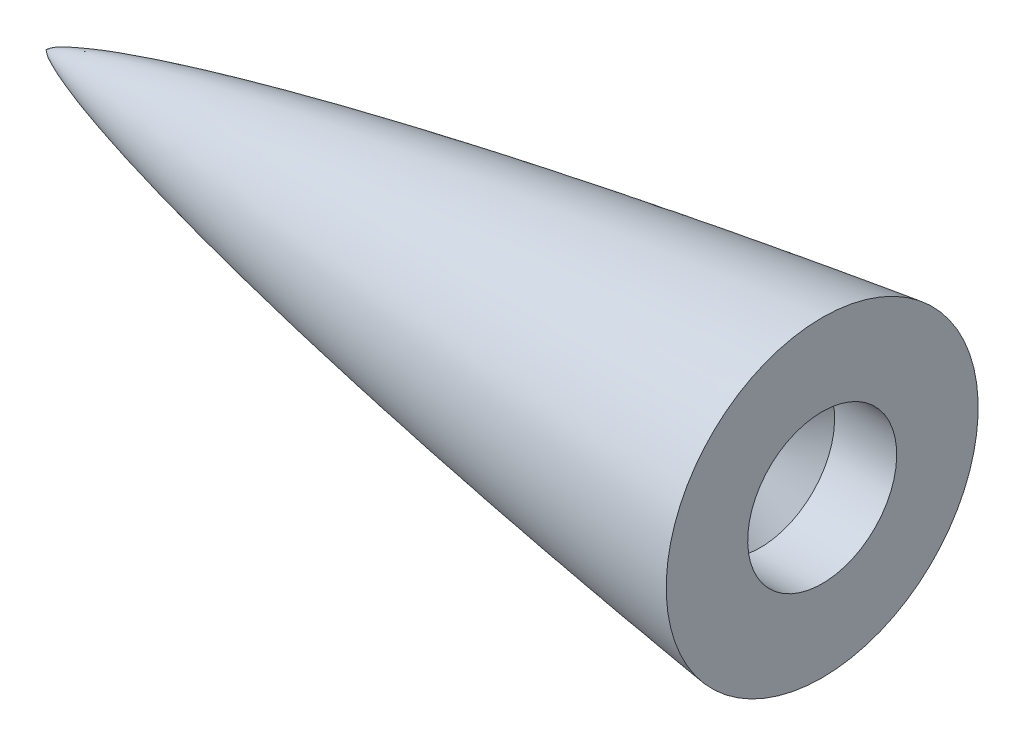
SolidWorks part; units mm, degrees
ref_plane "Front Plane" through (0, 0, 0) normal (0, 0, 1) x (1, 0, 0)
ref_plane "Top Plane" through (0, 0, 0) normal (0, 1, 0) x (1, 0, 0)
ref_plane "Right Plane" through (0, 0, 0) normal (1, 0, 0) x (0, 0, -1)
curve "Curve1"
  spline degree 3 poles (0, 0, 0) (0.3238, 0.2558, 0) (0.9402, 0.7427, 0) (1.9959, 1.205, 0) (2.9891, 1.6586, 0) (3.9977, 2.0398, 0) (4.9964, 2.4132, 0) (5.9986, 2.7607, 0) (6.9987, 3.1004, 0) (7.9965, 3.4344, 0) (9.0008, 3.7373, 0) (9.9965, 4.055, 0) (11.0004, 4.3386, 0) (12, 4.6299, 0) (12.9986, 4.9215, 0) (13.9986, 5.202, 0) (15.0003, 5.4688, 0) (15.9984, 5.7426, 0) (17.0001, 5.9995, 0) (18.0001, 6.2594, 0) (18.9985, 6.5227, 0) (20.0004, 6.7686, 0) (20.9985, 7.0227, 0) (22.0002, 7.2591, 0) (22.9999, 7.5005, 0) (24.0003, 7.7389, 0) (24.9983, 7.9838, 0) (26.0019, 8.205, 0) (26.9969, 8.4568, 0) (28.0017, 8.6659, 0) (28.9999, 8.9005, 0) (29.9988, 9.1322, 0) (31.0001, 9.3496, 0) (32.0002, 9.5692, 0) (32.9985, 9.7935, 0) (34.0016, 9.9959, 0) (34.9985, 10.2236, 0) (36.0002, 10.4289, 0) (36.9999, 10.6405, 0) (38.0002, 10.8489, 0) (38.9986, 11.0636, 0) (40.0015, 11.2559, 0) (40.9986, 11.4736, 0) (42.0002, 11.6689, 0) (42.9999, 11.8705, 0) (44.0002, 12.0689, 0) (44.9986, 12.2737, 0) (46.0015, 12.4556, 0) (46.9985, 12.6646, 0) (48.0015, 12.8456, 0) (48.9986, 13.0537, 0) (50.0002, 13.2389, 0) (50.9999, 13.4305, 0) (52.0002, 13.619, 0) (52.9988, 13.8134, 0) (54.0012, 13.9868, 0) (55, 14.1802, 0) (55.9989, 14.3724, 0) (57.0001, 14.5493, 0) (58, 14.7302, 0) (59, 14.9099, 0) (60, 15.09, 0) (61, 15.2699, 0) (62, 15.4503, 0) (63.0002, 15.629, 0) (63.9988, 15.8137, 0) (65.0013, 15.9758, 0) (65.9988, 16.1637, 0) (67.0002, 16.329, 0) (68, 16.5003, 0) (69, 16.6699, 0) (70, 16.84, 0) (71, 17.01, 0) (72, 17.1799, 0) (73, 17.3503, 0) (74.0002, 17.519, 0) (74.9988, 17.6937, 0) (76.0012, 17.8458, 0) (76.9989, 18.0234, 0) (78, 18.1799, 0) (79.0011, 18.3368, 0) (79.9989, 18.5134, 0) (81.0002, 18.6691, 0) (82, 18.8303, 0) (83, 18.9899, 0) (84, 19.1503, 0) (85.0001, 19.3091, 0) (85.999, 19.4734, 0) (87.001, 19.6168, 0) (88, 19.78, 0) (88.999, 19.9434, 0) (90.0012, 20.0859, 0) (90.999, 20.2534, 0) (92, 20.4, 0) (93.001, 20.5468, 0) (93.999, 20.7134, 0) (95.0001, 20.8591, 0) (96, 21.0103, 0) (97, 21.1599, 0) (98, 21.3103, 0) (99.0001, 21.4591, 0) (99.999, 21.6134, 0) (101.001, 21.7468, 0) (102, 21.8999, 0) (102.999, 22.0535, 0) (104.0011, 22.1855, 0) (104.9988, 22.3446, 0) (106.0011, 22.4755, 0) (106.999, 22.6335, 0) (108, 22.7699, 0) (109.001, 22.9068, 0) (109.999, 23.0634, 0) (111.0001, 23.1991, 0) (112, 23.3402, 0) (113, 23.48, 0) (114, 23.62, 0) (115, 23.7602, 0) (116.0001, 23.8991, 0) (116.9991, 24.0435, 0) (118.0009, 24.1667, 0) (119, 24.3099, 0) (119.9991, 24.4535, 0) (121.0011, 24.5755, 0) (121.9989, 24.7247, 0) (123.0011, 24.8455, 0) (123.9991, 24.9935, 0) (125, 25.1199, 0) (126.0009, 25.2467, 0) (126.9991, 25.3935, 0) (128.0001, 25.5191, 0) (129, 25.6503, 0) (130, 25.7799, 0) (131, 25.91, 0) (132, 26.0399, 0) (133, 26.1703, 0) (134.0001, 26.2991, 0) (134.9991, 26.4335, 0) (136.0008, 26.5467, 0) (137, 26.6799, 0) (137.9991, 26.8136, 0) (139.001, 26.9255, 0) (139.999, 27.0647, 0) (141.001, 27.1755, 0) (141.9991, 27.3136, 0) (143, 27.4299, 0) (144.0008, 27.5467, 0) (144.9991, 27.6835, 0) (146.0001, 27.7991, 0) (147, 27.9203, 0) (148, 28.0399, 0) (149, 28.16, 0) (150, 28.28, 0) (151, 28.4, 0) (152, 28.52, 0) (153, 28.6399, 0) (154, 28.7603, 0) (155.0001, 28.879, 0) (155.9992, 29.0038, 0) (157.0009, 29.1054, 0) (157.9991, 29.2348, 0) (159.0009, 29.3351, 0) (159.9991, 29.4649, 0) (161.0009, 29.5651, 0) (161.9991, 29.6948, 0) (163.0009, 29.7954, 0) (163.9992, 29.9238, 0) (165.0001, 30.029, 0) (166, 30.1403, 0) (167, 30.2499, 0) (168, 30.36, 0) (169, 30.47, 0) (170, 30.58, 0) (171, 30.69, 0) (172, 30.8, 0) (173, 30.9099, 0) (174, 31.0203, 0) (175.0001, 31.129, 0) (175.9992, 31.2439, 0) (177.0008, 31.3354, 0) (177.9991, 31.4548, 0) (179.0009, 31.5451, 0) (179.9991, 31.6649, 0) (181.0009, 31.7551, 0) (181.9991, 31.8748, 0) (183.0008, 31.9654, 0) (183.9992, 32.0838, 0) (185.0001, 32.179, 0) (186, 32.28, 0) (186.9999, 32.3809, 0) (188.0007, 32.4765, 0) (188.9993, 32.5935, 0) (190.0001, 32.6893, 0) (191.0001, 32.7893, 0) (191.9993, 32.8935, 0) (193.0007, 32.9764, 0) (193.9999, 33.0812, 0) (195.0001, 33.1788, 0) (195.9993, 33.2836, 0) (197.0006, 33.3667, 0) (198, 33.4699, 0) (198.9993, 33.5736, 0) (200.0007, 33.6554, 0) (200.9992, 33.7648, 0) (202.0008, 33.8454, 0) (202.9993, 33.9539, 0) (204.0001, 34.0387, 0) (204.9999, 34.1313, 0) (206.0007, 34.2163, 0) (206.9993, 34.3236, 0) (208.0001, 34.409, 0) (209, 34.5003, 0) (210, 34.5899, 0) (211, 34.6803, 0) (212.0001, 34.769, 0) (212.9994, 34.8635, 0) (214.0006, 34.9366, 0) (215, 35.03, 0) (215.9994, 35.1233, 0) (217.0006, 35.1967, 0) (218, 35.2899, 0) (218.9994, 35.3835, 0) (220.0006, 35.4558, 0) (220.9994, 35.5535, 0) (222, 35.6299, 0) (223.0006, 35.7067, 0) (223.9994, 35.8035, 0) (225.0001, 35.879, 0) (226, 35.9603, 0) (227, 36.0399, 0) (228, 36.12, 0) (229, 36.2, 0) (230, 36.2799, 0) (231, 36.3603, 0) (232.0001, 36.439, 0) (232.9995, 36.5235, 0) (234.0005, 36.5867, 0) (235, 36.6699, 0) (235.9995, 36.7535, 0) (237.0006, 36.8157, 0) (237.9995, 36.9035, 0) (239, 36.9699, 0) (240.0005, 37.0367, 0) (240.9995, 37.1235, 0) (242.0001, 37.189, 0) (243, 37.2603, 0) (244, 37.3299, 0) (245, 37.4, 0) (246, 37.47, 0) (247, 37.5399, 0) (248, 37.6103, 0) (249.0001, 37.6789, 0) (249.9995, 37.7539, 0) (251.0005, 37.8053, 0) (251.9995, 37.8849, 0) (253.0005, 37.9351, 0) (253.9995, 38.0149, 0) (255.0005, 38.0653, 0) (255.9995, 38.1439, 0) (257.0001, 38.1989, 0) (258, 38.2603, 0) (259, 38.3199, 0) (260, 38.38, 0) (261, 38.4399, 0) (262, 38.5003, 0) (263.0001, 38.5589, 0) (263.9996, 38.6239, 0) (265.0004, 38.6653, 0) (265.9995, 38.7349, 0) (267.0005, 38.7751, 0) (267.9995, 38.8449, 0) (269.0004, 38.8853, 0) (269.9996, 38.9539, 0) (271.0001, 38.999, 0) (272, 39.0502, 0) (273, 39.1002, 0) (274, 39.1491, 0) (274.9997, 39.2036, 0) (276.0003, 39.2365, 0) (277, 39.2903, 0) (277.9997, 39.3424, 0) (279, 39.3803, 0) (280.0003, 39.4166, 0) (280.9997, 39.4735, 0) (282, 39.5093, 0) (283, 39.5493, 0) (283.9998, 39.5935, 0) (285.0002, 39.6166, 0) (286, 39.6602, 0) (286.9998, 39.7026, 0) (288, 39.7293, 0) (289, 39.7602, 0) (290, 39.7899, 0) (291, 39.8203, 0) (292, 39.849, 0) (292.9998, 39.8839, 0) (294.0002, 39.8955, 0) (294.9998, 39.9341, 0) (296, 39.9482, 0) (296.9999, 39.9732, 0) (298, 39.9792, 0) (299, 39.9902, 0) (299.6667, 39.9967, 0) (300, 40, 0) knots 0 0 0 0 0.004059 0.007728 0.011327 0.014863 0.018375 0.021865 0.025345 0.028814 0.032263 0.035712 0.039142 0.042572 0.046002 0.049423 0.052835 0.056247 0.059651 0.063054 0.066458 0.069854 0.07325 0.076637 0.080025 0.083413 0.086801 0.090181 0.093569 0.096942 0.100322 0.103702 0.107075 0.110448 0.113821 0.117187 0.120561 0.123927 0.127293 0.130659 0.134025 0.137384 0.140751 0.14411 0.147469 0.150829 0.154188 0.157542 0.160901 0.164254 0.167614 0.170967 0.17432 0.177673 0.181027 0.184374 0.187727 0.19108 0.194427 0.197774 0.201122 0.204469 0.207816 0.211163 0.21451 0.217858 0.221199 0.224546 0.227888 0.231229 0.234571 0.237912 0.241254 0.244595 0.247937 0.251278 0.25462 0.257956 0.261298 0.264634 0.26797 0.271311 0.274648 0.277984 0.28132 0.284656 0.287992 0.291328 0.294659 0.297995 0.301332 0.304663 0.307999 0.31133 0.314661 0.317997 0.321328 0.324659 0.327991 0.331322 0.334653 0.337984 0.34131 0.344641 0.347972 0.351299 0.35463 0.357956 0.361287 0.364614 0.36794 0.371271 0.374598 0.377924 0.38125 0.384577 0.387903 0.391229 0.394556 0.397878 0.401204 0.404531 0.407853 0.411179 0.414501 0.417827 0.421149 0.424471 0.427798 0.43112 0.434442 0.437763 0.441085 0.444407 0.447729 0.451051 0.454373 0.457691 0.461013 0.464335 0.467653 0.470975 0.474293 0.477615 0.480933 0.484251 0.487573 0.49089 0.494208 0.497526 0.500844 0.504162 0.50748 0.510798 0.514116 0.517434 0.520751 0.524069 0.527383 0.530701 0.534015 0.537333 0.540647 0.543965 0.547279 0.550597 0.553911 0.557226 0.56054 0.563854 0.567168 0.570482 0.573796 0.57711 0.580424 0.583738 0.587053 0.590367 0.593677 0.596991 0.600302 0.603616 0.606927 0.610241 0.613552 0.616866 0.620177 0.623487 0.626798 0.630109 0.633423 0.636733 0.640044 0.643355 0.646662 0.649973 0.653284 0.656594 0.659902 0.663213 0.666523 0.669831 0.673142 0.676449 0.67976 0.683067 0.686375 0.689682 0.692993 0.696301 0.699608 0.702916 0.706223 0.709531 0.712838 0.716143 0.719451 0.722758 0.726063 0.729371 0.732678 0.735983 0.739291 0.742595 0.7459 0.749208 0.752513 0.755817 0.759122 0.762427 0.765732 0.769036 0.772341 0.775646 0.778951 0.782253 0.785558 0.788863 0.792165 0.79547 0.798772 0.802074 0.805379 0.808681 0.811984 0.815286 0.818588 0.821891 0.825193 0.828495 0.831797 0.8351 0.8384 0.841702 0.845002 0.848305 0.851605 0.854907 0.858207 0.861508 0.864808 0.868108 0.871408 0.874708 0.878008 0.881309 0.884607 0.887907 0.891206 0.894506 0.897804 0.901104 0.904403 0.907701 0.910999 0.914298 0.917596 0.920893 0.924191 0.92749 0.930787 0.934083 0.937382 0.940679 0.943976 0.947272 0.950568 0.953865 0.957162 0.960458 0.963753 0.967049 0.970345 0.973641 0.976936 0.980231 0.983527 0.986822 0.990117 0.993411 0.996706 1 1 1 1
sketch "Sketch1" plane through (0, 0, 0) normal (0, 0, 1) x (1, 0, 0)
  line L0 (125, 25.12) -> (125, 3.175)
  line L1 (21.825, 0) -> (0, 0)
  line L2 (1366, 0) -> (125, 0) construction
  line L3 (125, 3.175) -> (25, 3.175)
  line L4 (25, 3.175) -> (21.825, 0)
  line L5 (21.825, 0) -> (-59.4496, 0) construction
  line L6 (125, 12) -> (115, 12)
  line L7 (115, 12) -> (106.175, 3.175)
  spline S0 degree 3 poles (-1070.3353, 1688.9679) (10.2744, -68.4827) (-11.5783, -4.7393) (1.9959, 1.205) (2.9891, 1.6586) (3.9977, 2.0398) (4.9964, 2.4132) (5.9986, 2.7607) (6.9987, 3.1004) (7.9965, 3.4344) (9.0008, 3.7373) (9.9965, 4.055) (11.0004, 4.3386) (12, 4.6299) (12.9986, 4.9215) (13.9986, 5.202) (15.0003, 5.4688) (15.9984, 5.7426) (17.0001, 5.9995) (18.0001, 6.2594) (18.9985, 6.5227) (20.0004, 6.7686) (20.9985, 7.0227) (22.0002, 7.2591) (22.9999, 7.5005) (24.0003, 7.7389) (24.9983, 7.9838) (26.0019, 8.205) (26.9969, 8.4568) (28.0017, 8.6659) (28.9999, 8.9005) (29.9988, 9.1322) (31.0001, 9.3496) (32.0002, 9.5692) (32.9985, 9.7935) (34.0016, 9.9959) (34.9985, 10.2236) (36.0002, 10.4289) (36.9999, 10.6405) (38.0002, 10.8489) (38.9986, 11.0636) (40.0015, 11.2559) (40.9986, 11.4736) (42.0002, 11.6689) (42.9999, 11.8705) (44.0002, 12.0689) (44.9986, 12.2737) (46.0015, 12.4556) (46.9985, 12.6646) (48.0015, 12.8456) (48.9986, 13.0537) (50.0002, 13.2389) (50.9999, 13.4305) (52.0002, 13.619) (52.9988, 13.8134) (54.0012, 13.9868) (55, 14.1802) (55.9989, 14.3724) (57.0001, 14.5493) (58, 14.7302) (59, 14.9099) (60, 15.09) (61, 15.2699) (62, 15.4503) (63.0002, 15.629) (63.9988, 15.8137) (65.0013, 15.9758) (65.9988, 16.1637) (67.0002, 16.329) (68, 16.5003) (69, 16.6699) (70, 16.84) (71, 17.01) (72, 17.1799) (73, 17.3503) (74.0002, 17.519) (74.9988, 17.6937) (76.0012, 17.8458) (76.9989, 18.0234) (78, 18.1799) (79.0011, 18.3368) (79.9989, 18.5134) (81.0002, 18.6691) (82, 18.8303) (83, 18.9899) (84, 19.1503) (85.0001, 19.3091) (85.999, 19.4734) (87.001, 19.6168) (88, 19.78) (88.999, 19.9434) (90.0012, 20.0859) (90.999, 20.2534) (92, 20.4) (93.001, 20.5468) (93.999, 20.7134) (95.0001, 20.8591) (96, 21.0103) (97, 21.1599) (98, 21.3103) (99.0001, 21.4591) (99.999, 21.6134) (101.001, 21.7468) (102, 21.8999) (102.999, 22.0535) (104.0011, 22.1855) (104.9988, 22.3446) (106.0011, 22.4755) (106.999, 22.6335) (108, 22.7699) (109.001, 22.9068) (109.999, 23.0634) (111.0001, 23.1991) (112, 23.3402) (113, 23.48) (114, 23.62) (115, 23.7602) (116.0001, 23.8991) (116.9991, 24.0435) (118.0009, 24.1667) (119, 24.3099) (119.9991, 24.4535) (121.0011, 24.5755) (121.9989, 24.7247) (123.0011, 24.8455) (123.9991, 24.9935) (125, 25.1199) (126.0009, 25.2467) (126.9991, 25.3935) (128.0001, 25.5191) (129, 25.6503) (130, 25.7799) (131, 25.91) (132, 26.0399) (133, 26.1703) (134.0001, 26.2991) (134.9991, 26.4335) (136.0008, 26.5467) (137, 26.6799) (137.9991, 26.8136) (139.001, 26.9255) (139.999, 27.0647) (141.001, 27.1755) (141.9991, 27.3136) (143, 27.4299) (144.0008, 27.5467) (144.9991, 27.6835) (146.0001, 27.7991) (147, 27.9203) (148, 28.0399) (149, 28.16) (150, 28.28) (151, 28.4) (152, 28.52) (153, 28.6399) (154, 28.7603) (155.0001, 28.879) (155.9992, 29.0038) (157.0009, 29.1054) (157.9991, 29.2348) (159.0009, 29.3351) (159.9991, 29.4649) (161.0009, 29.5651) (161.9991, 29.6948) (163.0009, 29.7954) (163.9992, 29.9238) (165.0001, 30.029) (166, 30.1403) (167, 30.2499) (168, 30.36) (169, 30.47) (170, 30.58) (171, 30.69) (172, 30.8) (173, 30.9099) (174, 31.0203) (175.0001, 31.129) (175.9992, 31.2439) (177.0008, 31.3354) (177.9991, 31.4548) (179.0009, 31.5451) (179.9991, 31.6649) (181.0009, 31.7551) (181.9991, 31.8748) (183.0008, 31.9654) (183.9992, 32.0838) (185.0001, 32.179) (186, 32.28) (186.9999, 32.3809) (188.0007, 32.4765) (188.9993, 32.5935) (190.0001, 32.6893) (191.0001, 32.7893) (191.9993, 32.8935) (193.0007, 32.9764) (193.9999, 33.0812) (195.0001, 33.1788) (195.9993, 33.2836) (197.0006, 33.3667) (198, 33.4699) (198.9993, 33.5736) (200.0007, 33.6554) (200.9992, 33.7648) (202.0008, 33.8454) (202.9993, 33.9539) (204.0001, 34.0387) (204.9999, 34.1313) (206.0007, 34.2163) (206.9993, 34.3236) (208.0001, 34.409) (209, 34.5003) (210, 34.5899) (211, 34.6803) (212.0001, 34.769) (212.9994, 34.8635) (214.0006, 34.9366) (215, 35.03) (215.9994, 35.1233) (217.0006, 35.1967) (218, 35.2899) (218.9994, 35.3835) (220.0006, 35.4558) (220.9994, 35.5535) (222, 35.6299) (223.0006, 35.7067) (223.9994, 35.8035) (225.0001, 35.879) (226, 35.9603) (227, 36.0399) (228, 36.12) (229, 36.2) (230, 36.2799) (231, 36.3603) (232.0001, 36.439) (232.9995, 36.5235) (234.0005, 36.5867) (235, 36.6699) (235.9995, 36.7535) (237.0006, 36.8157) (237.9995, 36.9035) (239, 36.9699) (240.0005, 37.0367) (240.9995, 37.1235) (242.0001, 37.189) (243, 37.2603) (244, 37.3299) (245, 37.4) (246, 37.47) (247, 37.5399) (248, 37.6103) (249.0001, 37.6789) (249.9995, 37.7539) (251.0005, 37.8053) (251.9995, 37.8849) (253.0005, 37.9351) (253.9995, 38.0149) (255.0005, 38.0653) (255.9995, 38.1439) (257.0001, 38.1989) (258, 38.2603) (259, 38.3199) (260, 38.38) (261, 38.4399) (262, 38.5003) (263.0001, 38.5589) (263.9996, 38.6239) (265.0004, 38.6653) (265.9995, 38.7349) (267.0005, 38.7751) (267.9995, 38.8449) (269.0004, 38.8853) (269.9996, 38.9539) (271.0001, 38.999) (272, 39.0502) (273, 39.1002) (274, 39.1491) (274.9997, 39.2036) (276.0003, 39.2365) (277, 39.2903) (277.9997, 39.3424) (279, 39.3803) (280.0003, 39.4166) (280.9997, 39.4735) (282, 39.5093) (283, 39.5493) (283.9998, 39.5935) (285.0002, 39.6166) (286, 39.6602) (286.9998, 39.7026) (288, 39.7293) (289, 39.7602) (290, 39.7899) (291, 39.8203) (292, 39.849) (292.9998, 39.8839) (294.0002, 39.8955) (294.9998, 39.9341) (296, 39.9482) (296.9999, 39.9732) (298, 39.9792) (369.4003, 40.7684) (440.6193, 31.9722) (479.6754, 2027.9914) knots -0.134313 -0.134313 -0.134313 -0.134313 0.004059 0.007728 0.011327 0.014863 0.018375 0.021865 0.025345 0.028814 0.032263 0.035712 0.039142 0.042572 0.046002 0.049423 0.052835 0.056247 0.059651 0.063054 0.066458 0.069854 0.07325 0.076637 0.080025 0.083413 0.086801 0.090181 0.093569 0.096942 0.100322 0.103702 0.107075 0.110448 0.113821 0.117187 0.120561 0.123927 0.127293 0.130659 0.134025 0.137384 0.140751 0.14411 0.147469 0.150829 0.154188 0.157542 0.160901 0.164254 0.167614 0.170967 0.17432 0.177673 0.181027 0.184374 0.187727 0.19108 0.194427 0.197774 0.201122 0.204469 0.207816 0.211163 0.21451 0.217858 0.221199 0.224546 0.227888 0.231229 0.234571 0.237912 0.241254 0.244595 0.247937 0.251278 0.25462 0.257956 0.261298 0.264634 0.26797 0.271311 0.274648 0.277984 0.28132 0.284656 0.287992 0.291328 0.294659 0.297995 0.301332 0.304663 0.307999 0.31133 0.314661 0.317997 0.321328 0.324659 0.327991 0.331322 0.334653 0.337984 0.34131 0.344641 0.347972 0.351299 0.35463 0.357956 0.361287 0.364614 0.36794 0.371271 0.374598 0.377924 0.38125 0.384577 0.387903 0.391229 0.394556 0.397878 0.401204 0.404531 0.407853 0.411179 0.414501 0.417827 0.421149 0.424471 0.427798 0.43112 0.434442 0.437763 0.441085 0.444407 0.447729 0.451051 0.454373 0.457691 0.461013 0.464335 0.467653 0.470975 0.474293 0.477615 0.480933 0.484251 0.487573 0.49089 0.494208 0.497526 0.500844 0.504162 0.50748 0.510798 0.514116 0.517434 0.520751 0.524069 0.527383 0.530701 0.534015 0.537333 0.540647 0.543965 0.547279 0.550597 0.553911 0.557226 0.56054 0.563854 0.567168 0.570482 0.573796 0.57711 0.580424 0.583738 0.587053 0.590367 0.593677 0.596991 0.600302 0.603616 0.606927 0.610241 0.613552 0.616866 0.620177 0.623487 0.626798 0.630109 0.633423 0.636733 0.640044 0.643355 0.646662 0.649973 0.653284 0.656594 0.659902 0.663213 0.666523 0.669831 0.673142 0.676449 0.67976 0.683067 0.686375 0.689682 0.692993 0.696301 0.699608 0.702916 0.706223 0.709531 0.712838 0.716143 0.719451 0.722758 0.726063 0.729371 0.732678 0.735983 0.739291 0.742595 0.7459 0.749208 0.752513 0.755817 0.759122 0.762427 0.765732 0.769036 0.772341 0.775646 0.778951 0.782253 0.785558 0.788863 0.792165 0.79547 0.798772 0.802074 0.805379 0.808681 0.811984 0.815286 0.818588 0.821891 0.825193 0.828495 0.831797 0.8351 0.8384 0.841702 0.845002 0.848305 0.851605 0.854907 0.858207 0.861508 0.864808 0.868108 0.871408 0.874708 0.878008 0.881309 0.884607 0.887907 0.891206 0.894506 0.897804 0.901104 0.904403 0.907701 0.910999 0.914298 0.917596 0.920893 0.924191 0.92749 0.930787 0.934083 0.937382 0.940679 0.943976 0.947272 0.950568 0.953865 0.957162 0.960458 0.963753 0.967049 0.970345 0.973641 0.976936 0.980231 0.983527 0.986822 0.990117 0.993411 0.996706 1.695794 1.695794 1.695794 1.695794 only from (0, 0) to (300, 40) construction
  spline S1 degree 3 poles (0, 0) (0.3238, 0.2558) (0.9402, 0.7427) (1.9959, 1.205) (2.9891, 1.6586) (3.9977, 2.0398) (4.9964, 2.4132) (5.9986, 2.7607) (6.9987, 3.1004) (7.9965, 3.4344) (9.0008, 3.7373) (9.9965, 4.055) (11.0004, 4.3386) (12, 4.6299) (12.9986, 4.9215) (13.9986, 5.202) (15.0003, 5.4688) (15.9984, 5.7426) (17.0001, 5.9995) (18.0001, 6.2594) (18.9985, 6.5227) (20.0004, 6.7686) (20.9985, 7.0227) (22.0002, 7.2591) (22.9999, 7.5005) (24.0003, 7.7389) (24.9983, 7.9838) (26.0019, 8.205) (26.9969, 8.4568) (28.0017, 8.6659) (28.9999, 8.9005) (29.9988, 9.1322) (31.0001, 9.3496) (32.0002, 9.5692) (32.9985, 9.7935) (34.0016, 9.9959) (34.9985, 10.2236) (36.0002, 10.4289) (36.9999, 10.6405) (38.0002, 10.8489) (38.9986, 11.0636) (40.0015, 11.2559) (40.9986, 11.4736) (42.0002, 11.6689) (42.9999, 11.8705) (44.0002, 12.0689) (44.9986, 12.2737) (46.0015, 12.4556) (46.9985, 12.6646) (48.0015, 12.8456) (48.9986, 13.0537) (50.0002, 13.2389) (50.9999, 13.4305) (52.0002, 13.619) (52.9988, 13.8134) (54.0012, 13.9868) (55, 14.1802) (55.9989, 14.3724) (57.0001, 14.5493) (58, 14.7302) (59, 14.9099) (60, 15.09) (61, 15.2699) (62, 15.4503) (63.0002, 15.629) (63.9988, 15.8137) (65.0013, 15.9758) (65.9988, 16.1637) (67.0002, 16.329) (68, 16.5003) (69, 16.6699) (70, 16.84) (71, 17.01) (72, 17.1799) (73, 17.3503) (74.0002, 17.519) (74.9988, 17.6937) (76.0012, 17.8458) (76.9989, 18.0234) (78, 18.1799) (79.0011, 18.3368) (79.9989, 18.5134) (81.0002, 18.6691) (82, 18.8303) (83, 18.9899) (84, 19.1503) (85.0001, 19.3091) (85.999, 19.4734) (87.001, 19.6168) (88, 19.78) (88.999, 19.9434) (90.0012, 20.0859) (90.999, 20.2534) (92, 20.4) (93.001, 20.5468) (93.999, 20.7134) (95.0001, 20.8591) (96, 21.0103) (97, 21.1599) (98, 21.3103) (99.0001, 21.4591) (99.999, 21.6134) (101.001, 21.7468) (102, 21.8999) (102.999, 22.0535) (104.0011, 22.1855) (104.9988, 22.3446) (106.0011, 22.4755) (106.999, 22.6335) (108, 22.7699) (109.001, 22.9068) (109.999, 23.0634) (111.0001, 23.1991) (112, 23.3402) (113, 23.48) (114, 23.62) (115, 23.7602) (116.0001, 23.8991) (116.9991, 24.0435) (118.0009, 24.1667) (119, 24.3099) (119.9991, 24.4535) (121.0011, 24.5755) (121.9989, 24.7247) (123.0011, 24.8455) (123.9991, 24.9935) (125, 25.1199) (126.0009, 25.2467) (126.9991, 25.3935) (128.0001, 25.5191) (129, 25.6503) (130, 25.7799) (131, 25.91) (132, 26.0399) (133, 26.1703) (134.0001, 26.2991) (134.9991, 26.4335) (136.0008, 26.5467) (137, 26.6799) (137.9991, 26.8136) (139.001, 26.9255) (139.999, 27.0647) (141.001, 27.1755) (141.9991, 27.3136) (143, 27.4299) (144.0008, 27.5467) (144.9991, 27.6835) (146.0001, 27.7991) (147, 27.9203) (148, 28.0399) (149, 28.16) (150, 28.28) (151, 28.4) (152, 28.52) (153, 28.6399) (154, 28.7603) (155.0001, 28.879) (155.9992, 29.0038) (157.0009, 29.1054) (157.9991, 29.2348) (159.0009, 29.3351) (159.9991, 29.4649) (161.0009, 29.5651) (161.9991, 29.6948) (163.0009, 29.7954) (163.9992, 29.9238) (165.0001, 30.029) (166, 30.1403) (167, 30.2499) (168, 30.36) (169, 30.47) (170, 30.58) (171, 30.69) (172, 30.8) (173, 30.9099) (174, 31.0203) (175.0001, 31.129) (175.9992, 31.2439) (177.0008, 31.3354) (177.9991, 31.4548) (179.0009, 31.5451) (179.9991, 31.6649) (181.0009, 31.7551) (181.9991, 31.8748) (183.0008, 31.9654) (183.9992, 32.0838) (185.0001, 32.179) (186, 32.28) (186.9999, 32.3809) (188.0007, 32.4765) (188.9993, 32.5935) (190.0001, 32.6893) (191.0001, 32.7893) (191.9993, 32.8935) (193.0007, 32.9764) (193.9999, 33.0812) (195.0001, 33.1788) (195.9993, 33.2836) (197.0006, 33.3667) (198, 33.4699) (198.9993, 33.5736) (200.0007, 33.6554) (200.9992, 33.7648) (202.0008, 33.8454) (202.9993, 33.9539) (204.0001, 34.0387) (204.9999, 34.1313) (206.0007, 34.2163) (206.9993, 34.3236) (208.0001, 34.409) (209, 34.5003) (210, 34.5899) (211, 34.6803) (212.0001, 34.769) (212.9994, 34.8635) (214.0006, 34.9366) (215, 35.03) (215.9994, 35.1233) (217.0006, 35.1967) (218, 35.2899) (218.9994, 35.3835) (220.0006, 35.4558) (220.9994, 35.5535) (222, 35.6299) (223.0006, 35.7067) (223.9994, 35.8035) (225.0001, 35.879) (226, 35.9603) (227, 36.0399) (228, 36.12) (229, 36.2) (230, 36.2799) (231, 36.3603) (232.0001, 36.439) (232.9995, 36.5235) (234.0005, 36.5867) (235, 36.6699) (235.9995, 36.7535) (237.0006, 36.8157) (237.9995, 36.9035) (239, 36.9699) (240.0005, 37.0367) (240.9995, 37.1235) (242.0001, 37.189) (243, 37.2603) (244, 37.3299) (245, 37.4) (246, 37.47) (247, 37.5399) (248, 37.6103) (249.0001, 37.6789) (249.9995, 37.7539) (251.0005, 37.8053) (251.9995, 37.8849) (253.0005, 37.9351) (253.9995, 38.0149) (255.0005, 38.0653) (255.9995, 38.1439) (257.0001, 38.1989) (258, 38.2603) (259, 38.3199) (260, 38.38) (261, 38.4399) (262, 38.5003) (263.0001, 38.5589) (263.9996, 38.6239) (265.0004, 38.6653) (265.9995, 38.7349) (267.0005, 38.7751) (267.9995, 38.8449) (269.0004, 38.8853) (269.9996, 38.9539) (271.0001, 38.999) (272, 39.0502) (273, 39.1002) (274, 39.1491) (274.9997, 39.2036) (276.0003, 39.2365) (277, 39.2903) (277.9997, 39.3424) (279, 39.3803) (280.0003, 39.4166) (280.9997, 39.4735) (282, 39.5093) (283, 39.5493) (283.9998, 39.5935) (285.0002, 39.6166) (286, 39.6602) (286.9998, 39.7026) (288, 39.7293) (289, 39.7602) (290, 39.7899) (291, 39.8203) (292, 39.849) (292.9998, 39.8839) (294.0002, 39.8955) (294.9998, 39.9341) (296, 39.9482) (296.9999, 39.9732) (298, 39.9792) (299, 39.9902) (299.6667, 39.9967) (300, 40) knots 0 0 0 0 0.004059 0.007728 0.011327 0.014863 0.018375 0.021865 0.025345 0.028814 0.032263 0.035712 0.039142 0.042572 0.046002 0.049423 0.052835 0.056247 0.059651 0.063054 0.066458 0.069854 0.07325 0.076637 0.080025 0.083413 0.086801 0.090181 0.093569 0.096942 0.100322 0.103702 0.107075 0.110448 0.113821 0.117187 0.120561 0.123927 0.127293 0.130659 0.134025 0.137384 0.140751 0.14411 0.147469 0.150829 0.154188 0.157542 0.160901 0.164254 0.167614 0.170967 0.17432 0.177673 0.181027 0.184374 0.187727 0.19108 0.194427 0.197774 0.201122 0.204469 0.207816 0.211163 0.21451 0.217858 0.221199 0.224546 0.227888 0.231229 0.234571 0.237912 0.241254 0.244595 0.247937 0.251278 0.25462 0.257956 0.261298 0.264634 0.26797 0.271311 0.274648 0.277984 0.28132 0.284656 0.287992 0.291328 0.294659 0.297995 0.301332 0.304663 0.307999 0.31133 0.314661 0.317997 0.321328 0.324659 0.327991 0.331322 0.334653 0.337984 0.34131 0.344641 0.347972 0.351299 0.35463 0.357956 0.361287 0.364614 0.36794 0.371271 0.374598 0.377924 0.38125 0.384577 0.387903 0.391229 0.394556 0.397878 0.401204 0.404531 0.407853 0.411179 0.414501 0.417827 0.421149 0.424471 0.427798 0.43112 0.434442 0.437763 0.441085 0.444407 0.447729 0.451051 0.454373 0.457691 0.461013 0.464335 0.467653 0.470975 0.474293 0.477615 0.480933 0.484251 0.487573 0.49089 0.494208 0.497526 0.500844 0.504162 0.50748 0.510798 0.514116 0.517434 0.520751 0.524069 0.527383 0.530701 0.534015 0.537333 0.540647 0.543965 0.547279 0.550597 0.553911 0.557226 0.56054 0.563854 0.567168 0.570482 0.573796 0.57711 0.580424 0.583738 0.587053 0.590367 0.593677 0.596991 0.600302 0.603616 0.606927 0.610241 0.613552 0.616866 0.620177 0.623487 0.626798 0.630109 0.633423 0.636733 0.640044 0.643355 0.646662 0.649973 0.653284 0.656594 0.659902 0.663213 0.666523 0.669831 0.673142 0.676449 0.67976 0.683067 0.686375 0.689682 0.692993 0.696301 0.699608 0.702916 0.706223 0.709531 0.712838 0.716143 0.719451 0.722758 0.726063 0.729371 0.732678 0.735983 0.739291 0.742595 0.7459 0.749208 0.752513 0.755817 0.759122 0.762427 0.765732 0.769036 0.772341 0.775646 0.778951 0.782253 0.785558 0.788863 0.792165 0.79547 0.798772 0.802074 0.805379 0.808681 0.811984 0.815286 0.818588 0.821891 0.825193 0.828495 0.831797 0.8351 0.8384 0.841702 0.845002 0.848305 0.851605 0.854907 0.858207 0.861508 0.864808 0.868108 0.871408 0.874708 0.878008 0.881309 0.884607 0.887907 0.891206 0.894506 0.897804 0.901104 0.904403 0.907701 0.910999 0.914298 0.917596 0.920893 0.924191 0.92749 0.930787 0.934083 0.937382 0.940679 0.943976 0.947272 0.950568 0.953865 0.957162 0.960458 0.963753 0.967049 0.970345 0.973641 0.976936 0.980231 0.983527 0.986822 0.990117 0.993411 0.996706 1 1 1 1
  point P9 (106.4777, 3.175)
  dimension "D1" = 175
  dimension "D2" = 135
  dimension "D3" = 100
  dimension "D4" = 3.175
  dimension "D5" = 135
  dimension "D6" = 12
  dimension "D7" = 10
revolve "Revolve1" add sketch "Sketch1" angle 360 about L2
